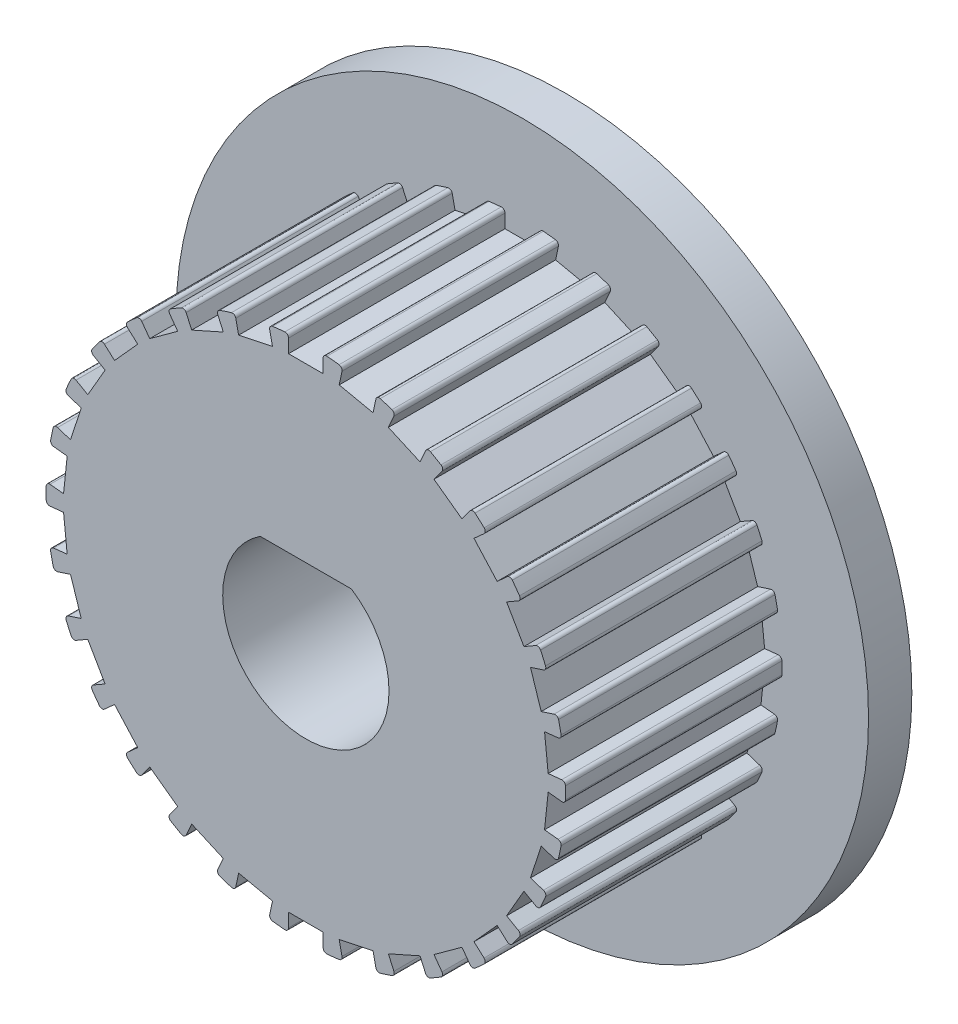
SolidWorks part; units mm, degrees
ref_plane "Front Plane" through (0, 0, 0) normal (0, 0, 1) x (1, 0, 0)
ref_plane "Top Plane" through (0, 0, 0) normal (0, 1, 0) x (1, 0, 0)
ref_plane "Right Plane" through (0, 0, 0) normal (1, 0, 0) x (0, 0, -1)
sketch "Sketch1" plane through (0, 0, 0) normal (0, 0, 1) x (1, 0, 0)
  circle A0 centre (0, 0) radius 12.7
  dimension "D1" = 25.4
extrude "Boss-Extrude1" add sketch "Sketch1" along normal blind 1.5875
sketch "Sketch2" plane through (0, 0, 1.5875) normal (0, 0, 1) x (1, 0, 0)
  circle A0 centre (0, 0) radius 9.525
  dimension "D1" = 19.05
extrude "Boss-Extrude2" add sketch "Sketch2" along normal blind 7.9375
sketch "Sketch3" plane through (0, 0, 9.525) normal (0, 0, 1) x (1, 0, 0)
  circle A0 centre (0, 0) radius 3.05
  dimension "D1" = 6.1
extrude "Cut-Extrude1" cut sketch "Sketch3" against normal through all
sketch "Sketch4" plane through (0, 0, 9.525) normal (0, 0, 1) x (1, 0, 0)
  line L0 (0, 8.8688) -> (0, 9.525) construction
  line L6 (-0.635, 9.5038) -> (0.635, 9.5038)
  line L7 (-0.635, 9.5038) -> (-0.635, 10.1388)
  line L8 (-0.635, 10.1388) -> (0.635, 10.1388)
  line L9 (0.635, 9.5038) -> (0.635, 10.1388)
  line L10 (-0.635, 9.5038) -> (0.635, 9.5038)
  line L11 (-0.635, 9.5038) -> (-0.635, 8.8688)
  line L12 (-0.635, 8.8688) -> (0.635, 8.8688)
  line L13 (0.635, 9.5038) -> (0.635, 8.8688)
  circle A0 centre (0, 0) radius 9.525 construction
  circle A5 centre (0, 0) radius 9.525 construction
  point P13 (0, 9.4966)
  dimension "D1" = 1.27
  dimension "D2" = 0.635
  dimension "D4" = 0.635
extrude "Cut-Extrude2" cut sketch "Sketch4" against normal up to surface (7.9375 mm away) contours L12 L13 L10 L11 | L7 L6 L9 L8 up to face at (9.525, 0, 1.5875)
fillet "Fillet2" radius 0.127 2 edges at (0.635, 9.5038, 5.5563) (-0.635, 9.5038, 5.5563)
pattern_circular "CirPattern1" count 30 over 360 about axis through (0, 0, 0) along (0, 0, 1) of "Cut-Extrude2", "Fillet2"
sketch "Sketch5" plane through (0, 0, 0) normal (0, 0, -1) x (-1, 0, 0)
  line L0 (-1.6733, 2.55) -> (1.6733, 2.55)
  circle A0 centre (0, 0) radius 3.05 construction
  arc A1 (-1.6733, 2.55) -> (1.6733, 2.55) centre (0, 0) cw
  point P5 (1.6084, 2.5914)
  point P6 (0, 0)
  point P9 (0, -3.05)
  dimension "D1" = 5.6
extrude "Boss-Extrude3" add sketch "Sketch5" against normal through all
